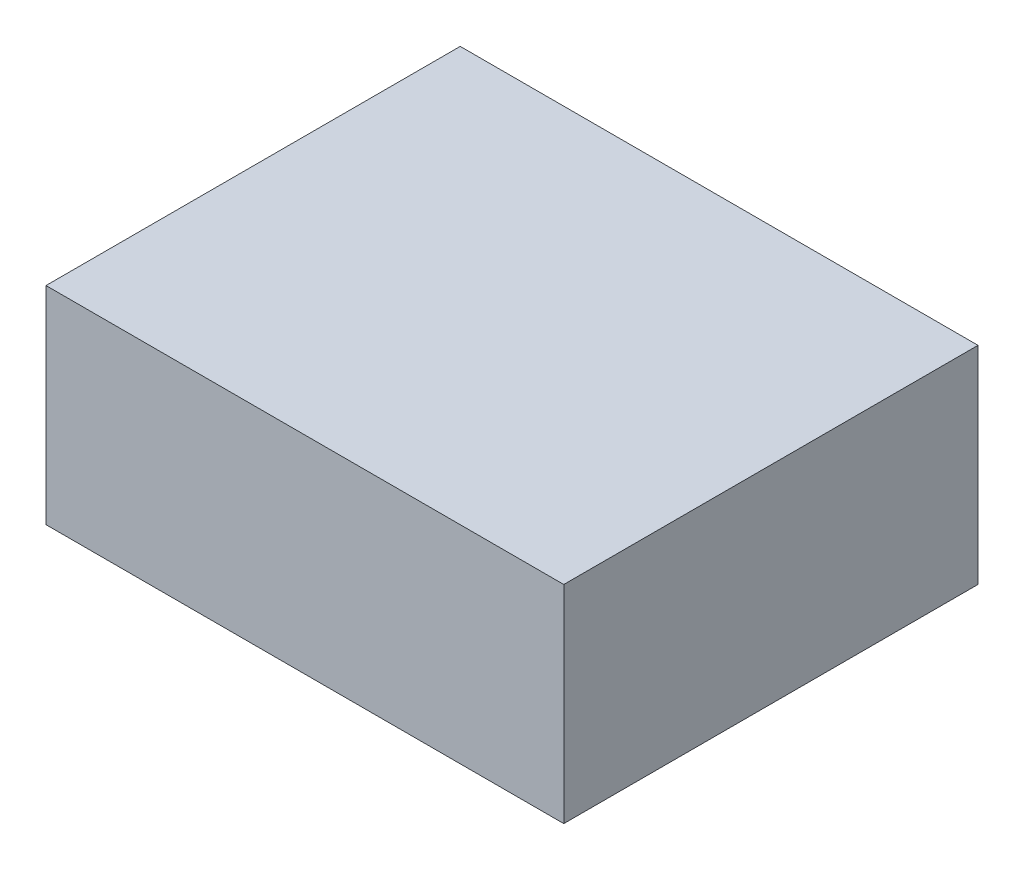
SolidWorks part; units mm, degrees
ref_plane "Plan de face" through (0, 0, 0) normal (0, 0, 1) x (1, 0, 0)
ref_plane "Plan de dessus" through (0, 0, 0) normal (0, 1, 0) x (1, 0, 0)
ref_plane "Plan de droite" through (0, 0, 0) normal (1, 0, 0) x (0, 0, -1)
sketch "Esquisse1" plane through (0, 0, 0) normal (0, 0, 1) x (1, 0, 0)
  line L1 (0, 0) -> (50, 0)
  line L2 (0, 0) -> (0, 20)
  line L3 (0, 20) -> (50, 20)
  line L4 (50, 0) -> (50, 20)
  dimension "D1" = 50
  dimension "D2" = 20
extrude "Boss.-Extru.1" add sketch "Esquisse1" along normal blind 40
